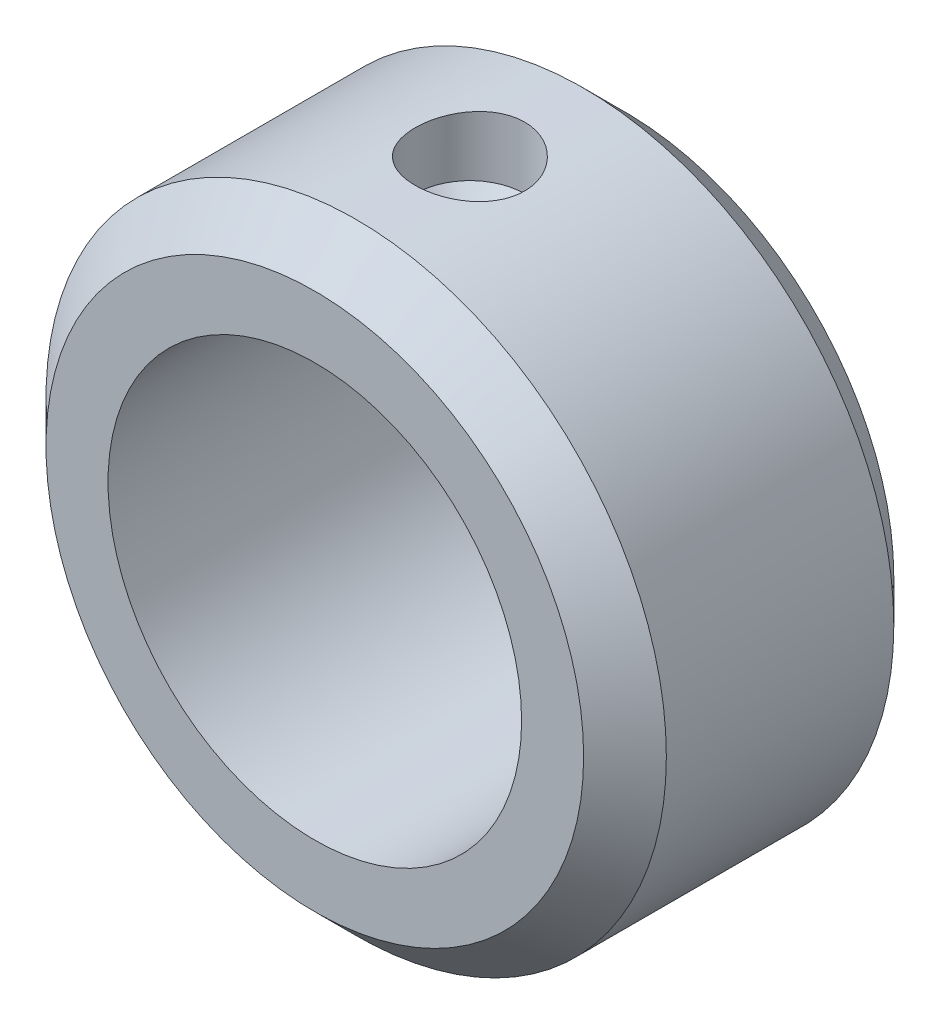
SolidWorks part; units mm, degrees
material "Сталь 40 ГОСТ 1050-60"
ref_plane "Спереди" through (0, 0, 0) normal (0, 0, 1) x (1, 0, 0)
ref_plane "Сверху" through (0, 0, 0) normal (0, 1, 0) x (1, 0, 0)
ref_plane "Справа" through (0, 0, 0) normal (1, 0, 0) x (0, 0, -1)
other "Configuration Table"
sketch "Эскиз1" plane through (0, 0, 0) normal (0, 0, 1) x (1, 0, 0)
  circle A0 centre (0, 0) radius 10
  circle A1 centre (0, 0) radius 15
  dimension "D1" = 20
  dimension "D2" = 30
extrude "Бобышка-Вытянуть1" add sketch "Эскиз1" along normal blind 15
chamfer "Фаска1" distance 2 angle 45 2 edges at (15, 0, 0) (15, 0, 15)
sketch "Эскиз2" plane through (0, 0, 0) normal (1, 0, 0) x (0, 0, -1)
  line L0 (-7.5, 15) -> (-10.15, 15)
  line L1 (-7.5, 0) -> (-7.5, 15) construction
  line L2 (-2, 15) -> (-13, 15) construction
  line L9 (-7.5, 15) -> (-7.5, 10.35)
  line L11 (-8.5, 10.35) -> (-10.15, 12)
  line L12 (-10.15, 12) -> (-10.15, 15)
  line L13 (-7.5, 10.35) -> (-8.5, 10.35)
  dimension "D1" = 2.65
  dimension "D2" = 7.5
  dimension "D3" = 8.5
  dimension "D4" = 45
  dimension "D5" = 10.35
revolve "Вырез-Повернуть1" cut sketch "Эскиз2" angle 360 about L1
cosmetic thread "Условное изображение резьбы1" parameters "D2"=8
